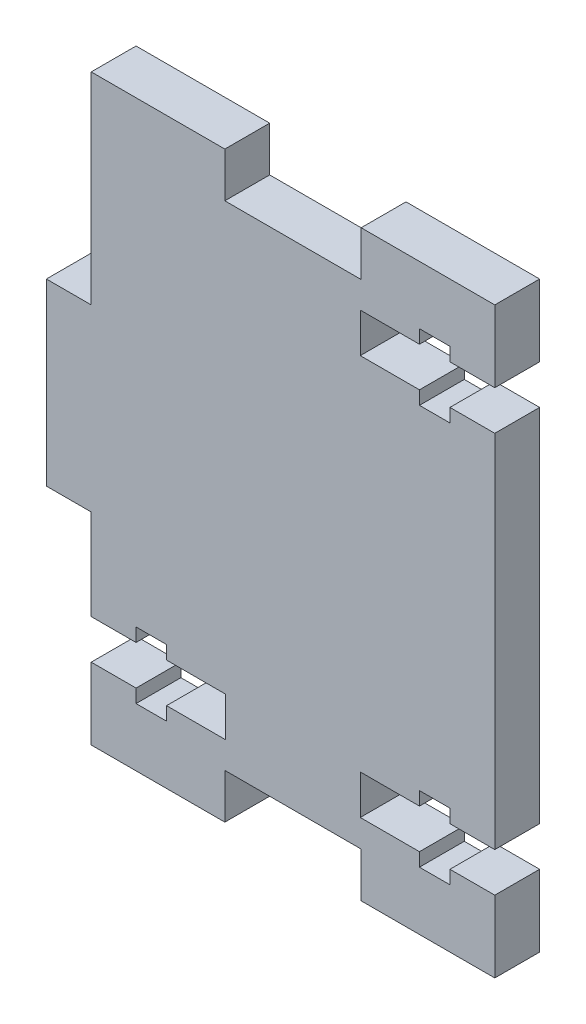
SolidWorks part; units mm, degrees
ref_plane "Front Plane" through (0, 0, 0) normal (0, 0, 1) x (1, 0, 0)
ref_plane "Top Plane" through (0, 0, 0) normal (0, 1, 0) x (1, 0, 0)
ref_plane "Right Plane" through (0, 0, 0) normal (1, 0, 0) x (0, 0, -1)
sketch "Sketch1" plane through (0, 0, 0) normal (0, 0, 1) x (1, 0, 0)
  line L1 (-22.5, 32.5) -> (0, 32.5)
  line L2 (-22.5, 32.5) -> (-22.5, 10)
  line L3 (-22.5, -32.5) -> (22.5, -32.5)
  line L4 (22.5, 32.5) -> (22.5, -32.5)
  line L7 (0, 32.5) -> (22.5, 32.5)
  line L8 (-22.5, -10) -> (-22.5, -32.5)
  line L9 (-22.5, 10) -> (-27.5, 10)
  line L11 (-22.5, -10) -> (-27.5, -10)
  line L12 (-27.5, 10) -> (-27.5, -10)
  dimension "D1" = 45
  dimension "D2" = 65
  dimension "D3" = 22.5
  dimension "D4" = 32.5
  dimension "D5" = 5
  dimension "D6" = 22.5
  dimension "D7" = 20
extrude "Boss-Extrude1" add sketch "Sketch1" along normal blind 5
sketch "Sketch3" plane through (0, 0, 5) normal (0, 0, 1) x (1, 0, 0)
  line L0 (0, 0) -> (28.1265, 0) construction
  line L13 (22.5, -32.5) -> (22.5, 32.5) construction
  line L14 (22.5, 24.5) -> (17.5, 24.5)
  line L15 (17.5, 24.5) -> (17.5, 26)
  line L16 (17.5, 26) -> (14.1, 26)
  line L17 (14.1, 26) -> (14.1, 24.5)
  line L18 (14.1, 24.5) -> (7.5, 24.5)
  line L19 (7.5, 24.5) -> (7.5, 20.1)
  line L20 (7.5, 20.1) -> (14.1, 20.1)
  line L21 (14.1, 20.1) -> (14.1, 18.6)
  line L22 (14.1, 18.6) -> (17.5, 18.6)
  line L23 (17.5, 18.6) -> (17.5, 20.1)
  line L24 (17.5, 20.1) -> (22.5, 20.1)
  line L25 (22.5, 24.5) -> (22.5, 20.1)
  line L26 (22.5, 32.5) -> (-22.5, 32.5) construction
  line L27 (0, 0) -> (0, 42.4523) construction
  line L28 (22.5, -24.5) -> (22.5, -20.1)
  line L29 (17.5, -20.1) -> (22.5, -20.1)
  line L30 (17.5, -18.6) -> (17.5, -20.1)
  line L31 (14.1, -18.6) -> (17.5, -18.6)
  line L32 (14.1, -20.1) -> (14.1, -18.6)
  line L33 (7.5, -20.1) -> (14.1, -20.1)
  line L34 (7.5, -24.5) -> (7.5, -20.1)
  line L35 (14.1, -24.5) -> (7.5, -24.5)
  line L36 (14.1, -26) -> (14.1, -24.5)
  line L37 (17.5, -26) -> (14.1, -26)
  line L38 (17.5, -24.5) -> (17.5, -26)
  line L39 (22.5, -24.5) -> (17.5, -24.5)
  line L40 (-22.5, -24.5) -> (-17.5, -24.5)
  line L41 (-17.5, -24.5) -> (-17.5, -26)
  line L42 (-17.5, -26) -> (-14.1, -26)
  line L43 (-14.1, -26) -> (-14.1, -24.5)
  line L44 (-14.1, -24.5) -> (-7.5, -24.5)
  line L45 (-7.5, -24.5) -> (-7.5, -20.1)
  line L46 (-7.5, -20.1) -> (-14.1, -20.1)
  line L47 (-14.1, -20.1) -> (-14.1, -18.6)
  line L48 (-14.1, -18.6) -> (-17.5, -18.6)
  line L49 (-17.5, -18.6) -> (-17.5, -20.1)
  line L50 (-17.5, -20.1) -> (-22.5, -20.1)
  line L51 (-22.5, -24.5) -> (-22.5, -20.1)
  dimension "D8" = 4.4
  dimension "D9" = 1.5
  dimension "D10" = 1.5
  dimension "D11" = 3.4
  dimension "D12" = 5
  dimension "D13" = 8
  dimension "D14" = 15
extrude "Cut-Extrude1" cut sketch "Sketch3" against normal blind 5
sketch "Sketch4" plane through (0, 0, 5) normal (0, 0, 1) x (1, 0, 0)
  line L1 (7.6, -32.5) -> (7.6, -27.5)
  line L3 (7.6, -27.5) -> (-7.6, -27.5)
  line L4 (-7.6, -27.5) -> (-7.6, -32.5)
  line L5 (-22.5, -32.5) -> (22.5, -32.5) construction
  line L6 (-7.6, -32.5) -> (7.6, -32.5)
  line L7 (22.5, -32.5) -> (22.5, -24.5) construction
  line L9 (0, 0) -> (24.7904, 0) construction
  line L10 (-7.6, 32.5) -> (7.6, 32.5)
  line L11 (-7.6, 27.5) -> (-7.6, 32.5)
  line L12 (7.6, 27.5) -> (-7.6, 27.5)
  line L13 (7.6, 32.5) -> (7.6, 27.5)
  dimension "D1" = 5
  dimension "D2" = 15.2
  dimension "D3" = 14.9
extrude "Cut-Extrude2" cut sketch "Sketch4" against normal blind 10
